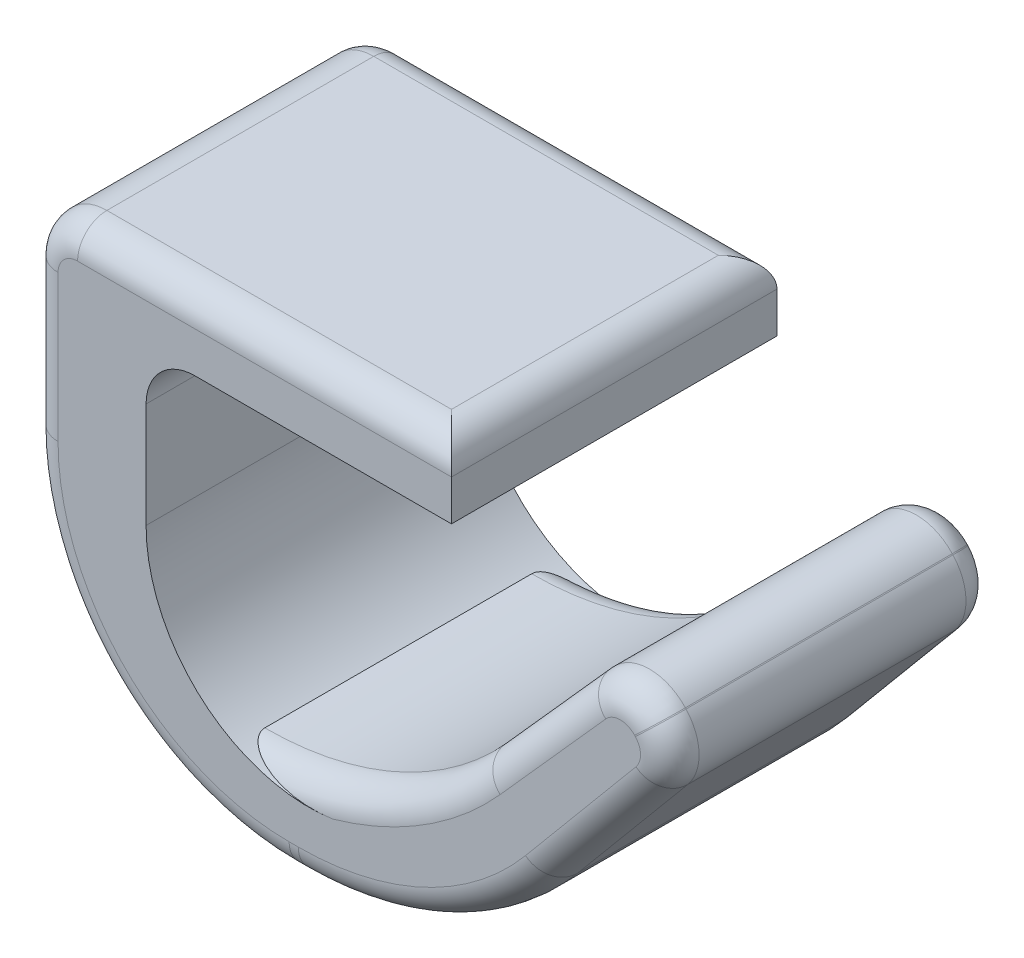
SolidWorks part; units mm, degrees
ref_plane "Alzado" through (0, 0, 0) normal (0, 0, 1) x (1, 0, 0)
ref_plane "Planta" through (0, 0, 0) normal (0, 1, 0) x (1, 0, 0)
ref_plane "Vista lateral" through (0, 0, 0) normal (1, 0, 0) x (0, 0, -1)
sketch "Croquis2" plane through (0, 0, 0) normal (0, 0, 1) x (1, 0, 0)
  line L0 (-5.7441, 0) -> (5.7441, 0)
  line L1 (-7.2441, -1.5) -> (-7.2441, -6)
  line L2 (0.7559, -14) -> (1.0372, -14)
  line L3 (8.7106, -10.4124) -> (12.1035, -6.3522)
  line L4 (5.7441, 0) -> (5.7441, -2.1475)
  line L5 (5.7441, -2.1475) -> (-2.1393, -2.1475)
  line L6 (-3.6393, -3.6475) -> (-3.6393, -6.8802)
  line L8 (6.5667, -8.0038) -> (9.8124, -4.3685)
  line L9 (12.0305, -4.3469) -> (12.0517, -4.3697)
  arc A0 (-7.2441, -6) -> (0.7559, -14) centre (0.7559, -6) ccw
  arc A1 (-0.8927, -11.3436) -> (-3.6393, -6.8802) centre (1.3607, -6.8802) cw
  arc A2 (8.7106, -10.4124) -> (1.0372, -14) centre (1.0372, -4) cw
  arc A3 (-0.8927, -11.3436) -> (6.5667, -8.0038) centre (-0.8927, -1.3436) ccw
  arc A4 (-2.1393, -2.1475) -> (-3.6393, -3.6475) centre (-2.1393, -3.6475) ccw
  arc A5 (-5.7441, 0) -> (-7.2441, -1.5) centre (-5.7441, -1.5) ccw
  arc A6 (12.0305, -4.3469) -> (9.8124, -4.3685) centre (10.9314, -5.3676) ccw
  arc A7 (12.0517, -4.3697) -> (12.1035, -6.3522) centre (10.9525, -5.3904) cw
  point P4 (0, 0)
  point P15 (-7.2441, -14)
  point P22 (0, 0)
  point P23 (0, 0)
  point P28 (10.9096, -3.1397)
  point P31 (12.951, -5.3381)
  dimension "D3" = 8
  dimension "D4" = 5
  dimension "D5" = 10
  dimension "D7" = 1.5
  dimension "D6" = 3
extrude "Saliente-Extruir1" add sketch "Croquis2" along normal blind 10
fillet "Redondeo8" radius 0.9 25 edges at (3.1938, -10.4705, 10) (8.1896, -6.1862, 10) (10.9167, -3.8676, 10) (12.0411, -4.3583, 10) (12.452, -5.3512, 10) (10.4071, -8.3823, 10) (5.2725, -13.0588, 10) (0.8966, -14, 10) (-4.9009, -11.6569, 10) (-7.2441, -3.75, 10) (-6.8047, -0.4393, 10) (3.1938, -10.4705, 0) (8.1896, -6.1862, 0) (10.9167, -3.8676, 0) (12.0411, -4.3583, 0) (12.452, -5.3512, 0) (10.4071, -8.3823, 0) (5.2725, -13.0588, 0) (0.8966, -14, 0) (-4.9009, -11.6569, 0) (-7.2441, -3.75, 0) (-6.8047, -0.4393, 0) (5.7441, 0, 5) (0, 0, 10) (0, 0, 0)
